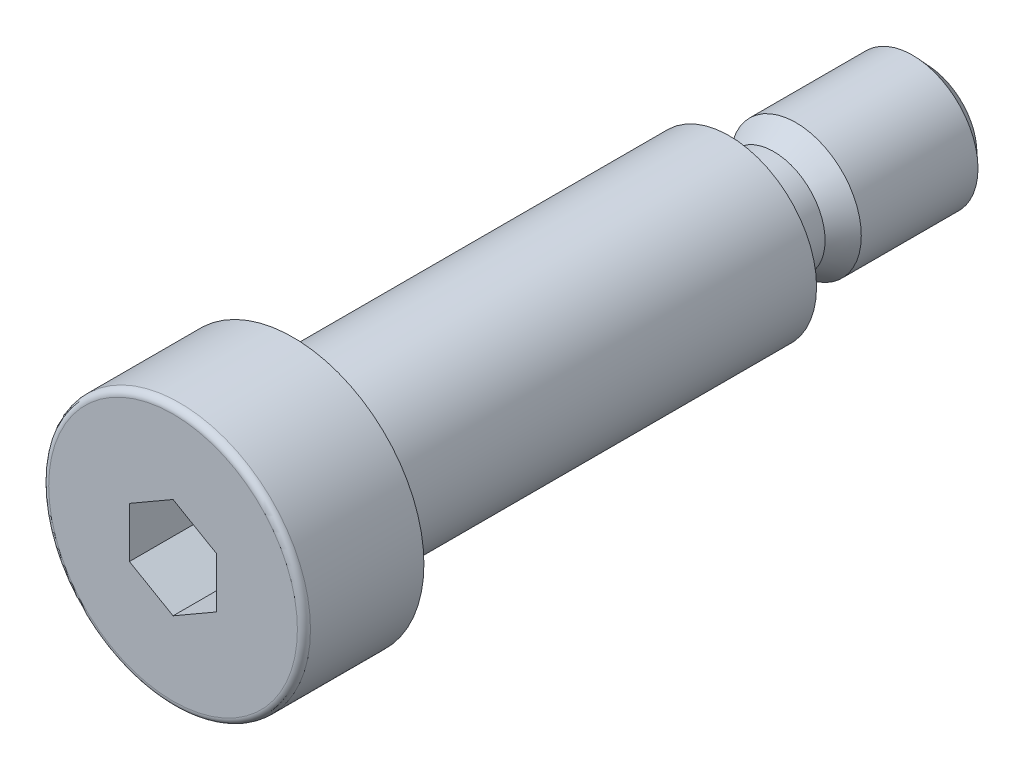
SolidWorks part; units mm, degrees
material "1.0545 (S355N)"
ref_plane "Płaszczyzna przednia" through (0, 0, 0) normal (0, 0, 1) x (1, 0, 0)
ref_plane "Płaszczyzna górna" through (0, 0, 0) normal (0, 1, 0) x (1, 0, 0)
ref_plane "Płaszczyzna prawa" through (0, 0, 0) normal (1, 0, 0) x (0, 0, -1)
sketch "Szkic1" plane through (0, 0, 0) normal (0, 1, 0) x (1, 0, 0)
  line L0 (6, 26.1) -> (4.7, 24.08)
  line L1 (12, -31) -> (-12, -31)
  line L2 (12, -31) -> (12, -20)
  line L3 (12, -20) -> (-12, -20)
  line L4 (-12, -31) -> (-12, -20)
  line L5 (8, -20) -> (-8, -20)
  line L6 (8, -20) -> (8, 20)
  line L7 (8, 20) -> (-8, 20)
  line L8 (-8, -20) -> (-8, 20)
  line L9 (-4.7, 20) -> (4.7, 20)
  line L10 (-4.7, 20) -> (-4.7, 24.08)
  line L11 (-4.7, 24.08) -> (4.7, 24.08)
  line L12 (4.7, 20) -> (4.7, 24.08)
  line L13 (6, 26.1) -> (6, 36.8)
  line L14 (6, 36.8) -> (4.7, 38)
  line L15 (4.7, 38) -> (-4.7, 38)
  line L16 (-4.7, 38) -> (-6, 36.8)
  line L17 (-6, 36.8) -> (-6, 26.1)
  line L18 (-6, 26.1) -> (-4.7, 24.08)
  line L19 (6, 26.1) -> (-6, 26.1) construction
  line L20 (6, 36.8) -> (-6, 36.8) construction
  line L21 (0, -19.9356) -> (0, 25.6583) construction
  line L22 (0, -31) -> (0, 38)
  point P4 (0, -20)
  point P14 (0, -20)
  point P15 (0, 20)
  point P16 (0, 20)
  point P17 (-8, 0)
  point P23 (0, 26.1)
  point P25 (0, 38)
  point P26 (0, 24.08)
  point P27 (0, 36.8)
  dimension "D1" = 24
  dimension "D2" = 11
  dimension "D3" = 16
  dimension "l1" = 40
  dimension "D5" = 9.4
  dimension "D6" = 18
  dimension "D7" = 12
  dimension "D8" = 9.4
  dimension "D9" = 1.2
  dimension "D10" = 2.02
  dimension "D11" = 10.7
revolve "Obrót1" add sketch "Szkic1" angle 360 about L22
sketch "Szkic2" plane through (0, 0, 31) normal (0, 0, 1) x (1, 0, 0)
  line L1 (4, 2.3094) -> (0, 4.6188)
  line L2 (0, 4.6188) -> (-4, 2.3094)
  line L3 (-4, 2.3094) -> (-4, -2.3094)
  line L4 (-4, -2.3094) -> (0, -4.6188)
  line L5 (0, -4.6188) -> (4, -2.3094)
  line L6 (4, -2.3094) -> (4, 2.3094)
  circle A0 centre (0, 0) radius 4 construction
  dimension "D1" = 8
extrude "Wytnij-wyciągnięcie1" cut sketch "Szkic2" against normal blind 6.6
fillet "Zaokrąglenie1" radius 0.6 1 edges at (12, 0, 31)
